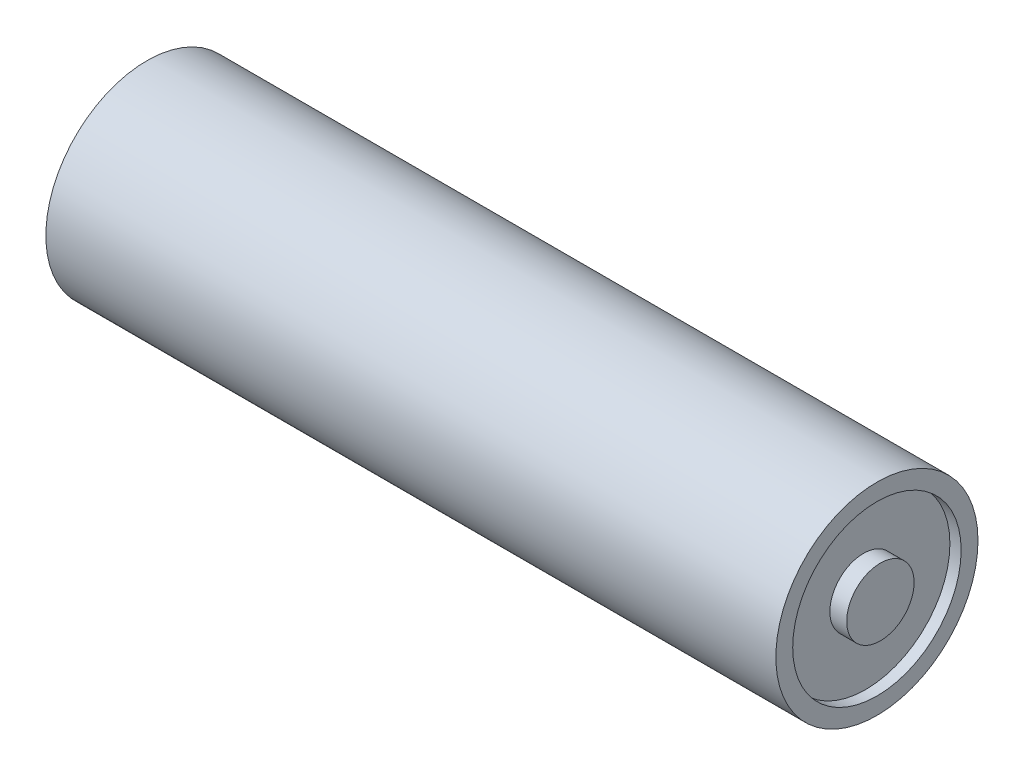
SolidWorks part; units mm, degrees
ref_plane "Спереди" through (0, 0, 0) normal (0, 0, 1) x (1, 0, 0)
ref_plane "Сверху" through (0, 0, 0) normal (0, 1, 0) x (1, 0, 0)
ref_plane "Справа" through (0, 0, 0) normal (1, 0, 0) x (0, 0, -1)
sketch "Эскиз1" plane through (0, 0, 0) normal (1, 0, 0) x (0, 0, -1)
  circle A0 centre (0, 0) radius 9
  dimension "D1" = 18
extrude "Бобышка-Вытянуть1" add sketch "Эскиз1" along normal blind 65
sketch "Эскиз2" plane through (65, 0, 0) normal (1, 0, 0) x (0, 0, -1)
  circle A0 centre (0, 0) radius 7.5
  dimension "D1" = 15
extrude "Вырез-Вытянуть1" cut sketch "Эскиз2" against normal blind 1
sketch "Эскиз3" plane through (64, 0, 0) normal (1, 0, 0) x (0, 0, -1)
  circle A0 centre (-0.1923, 0.1037) radius 3
extrude "Бобышка-Вытянуть2" add sketch "Эскиз3" along normal blind 1.5
